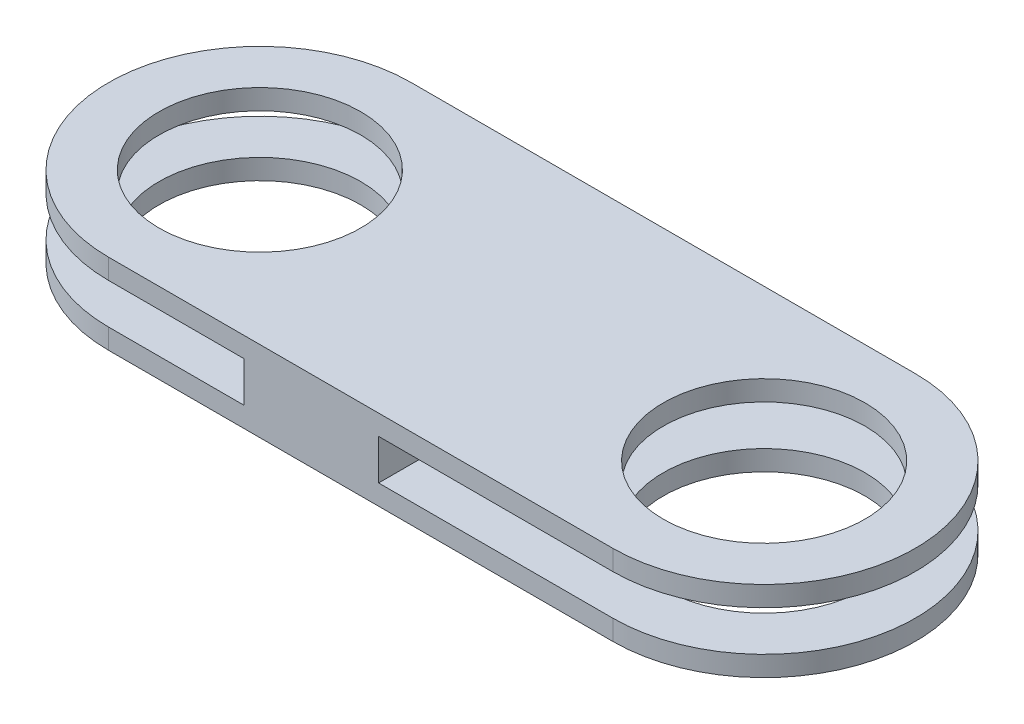
SolidWorks part; units mm, degrees
ref_plane "前视基准面" through (0, 0, 0) normal (0, 0, 1) x (1, 0, 0)
ref_plane "上视基准面" through (0, 0, 0) normal (0, 1, 0) x (1, 0, 0)
ref_plane "右视基准面" through (0, 0, 0) normal (1, 0, 0) x (0, 0, -1)
other "Configuration Table"
sketch "草图1" plane through (0, 0, 0) normal (0, 1, 0) x (1, 0, 0)
  line L0 (0, 0) -> (50, 0) construction
  line L1 (0, 15) -> (50, 15)
  line L2 (0, -15) -> (50, -15)
  arc A0 (0, 15) -> (0, -15) centre (0, 0) ccw
  arc A1 (50, -15) -> (50, 15) centre (50, 0) ccw
  circle A2 centre (0, 0) radius 10
  circle A3 centre (50, 0) radius 10
  point P3 (25, 0)
  dimension "D2" = 20
  dimension "20" = 20
  dimension "D1" = 50
  dimension "D4" = 30
extrude "凸台-拉伸1" add sketch "草图1" along normal blind 2
sketch "草图2" plane through (0, 2, 0) normal (0, 1, 0) x (1, 0, 0)
  line L0 (0, -15) -> (50, -15) construction
  line L1 (13.4192, 15) -> (26.7759, 15)
  line L2 (13.4192, 15) -> (13.4192, -15)
  line L3 (13.4192, -15) -> (26.7759, -15)
  line L4 (26.7759, 15) -> (26.7759, -15)
  line L5 (13.4192, 15) -> (26.7759, -15) construction
  line L6 (13.4192, -15) -> (26.7759, 15) construction
  point P0 (20.0976, 0)
  dimension "D1" = 30
extrude "凸台-拉伸2" add sketch "草图2" along normal blind 2
ref_plane "基准面2" through (0, 4, 0) normal (0, 1, 0) x (1, 0, 0)
mirror "镜向1" about plane through (0, 4, 0) normal (0, 1, 0) of "凸台-拉伸1", "凸台-拉伸2"
